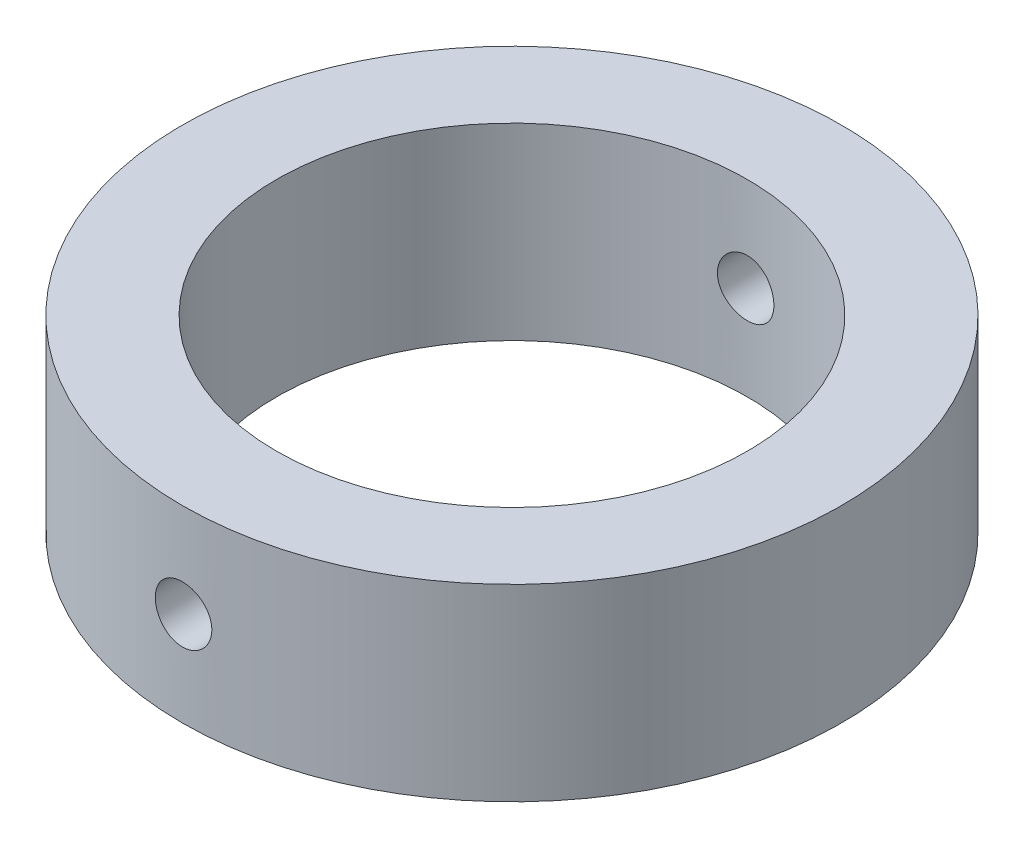
SolidWorks part; units mm, degrees
ref_plane "Front Plane" through (0, 0, 0) normal (0, 0, 1) x (1, 0, 0)
ref_plane "Top Plane" through (0, 0, 0) normal (0, 1, 0) x (1, 0, 0)
ref_plane "Right Plane" through (0, 0, 0) normal (1, 0, 0) x (0, 0, -1)
sketch "Sketch1" plane through (0, 0, 0) normal (0, 1, 0) x (1, 0, 0)
  circle A0 centre (0, 0) radius 35
  circle A1 centre (0, 0) radius 25
  dimension "D1" = 70
  dimension "D2" = 50
extrude "Boss-Extrude1" add sketch "Sketch1" along normal blind 20
sketch "Sketch2" plane through (0, 0, 0) normal (0, 0, 1) x (1, 0, 0)
  line L0 (-35, 20) -> (-35, 0) construction
  line L1 (35, 0) -> (35, 20) construction
  line L2 (-35, 0) -> (35, 0) construction
  line L3 (35, 20) -> (-35, 20) construction
  line L4 (-35, 20) -> (-35, 0)
  line L5 (35, 0) -> (35, 20)
  line L6 (-35, 0) -> (35, 0)
  line L7 (35, 20) -> (-35, 20)
  circle A0 centre (0, 10) radius 3
  dimension "D1" = 6
  dimension "D2" = 10
extrude "Cut-Extrude3" cut sketch "Sketch2" against normal through all both and the other way through all contours A0
